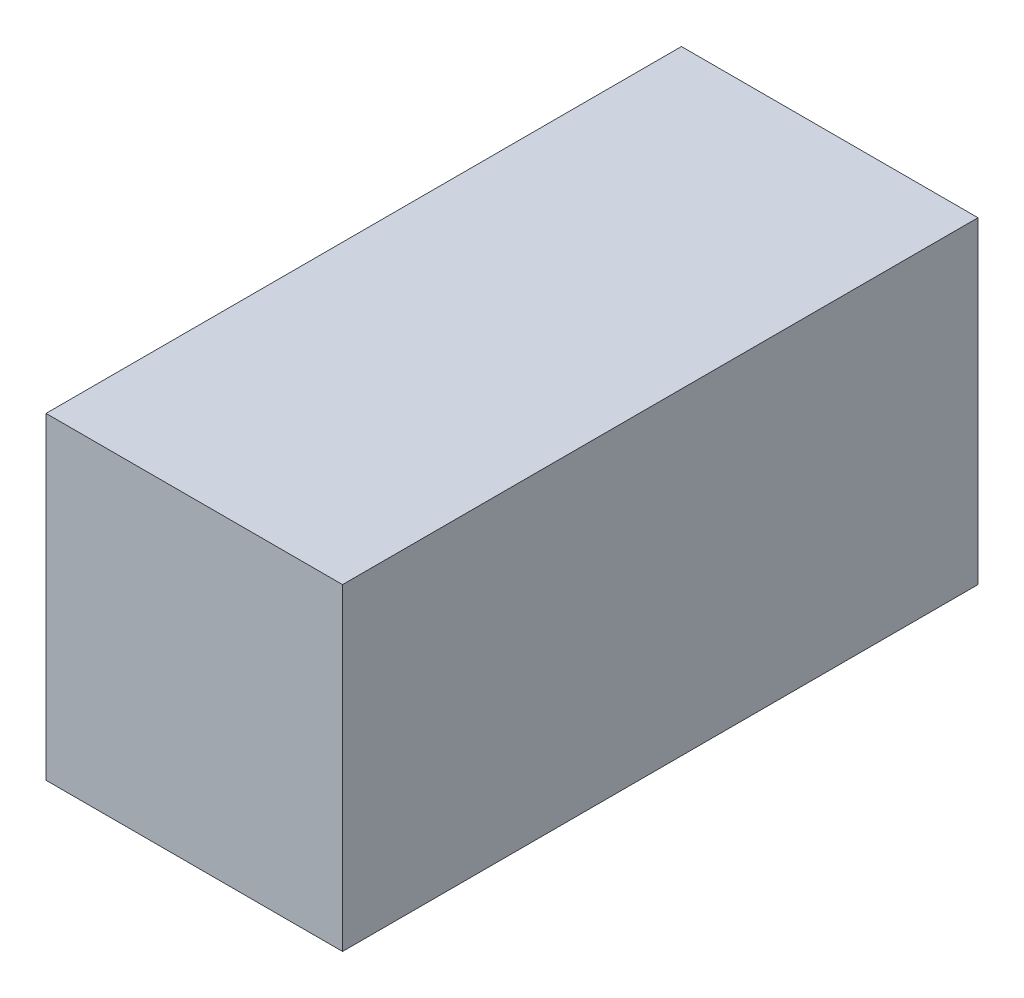
SolidWorks part; units mm, degrees
ref_plane "Front Plane" through (0, 0, 0) normal (0, 0, 1) x (1, 0, 0)
ref_plane "Top Plane" through (0, 0, 0) normal (0, 1, 0) x (1, 0, 0)
ref_plane "Right Plane" through (0, 0, 0) normal (1, 0, 0) x (0, 0, -1)
other "Configuration Table"
sketch "Sketch1" plane through (0, 0, 0) normal (0, 0, 1) x (1, 0, 0)
  line L1 (230, 405) -> (370, 405)
  line L2 (230, 405) -> (230, 555)
  line L3 (230, 555) -> (370, 555)
  line L4 (370, 405) -> (370, 555)
extrude "STORE_klape_kaset_kati_donmus_kap_2_1" add sketch "Sketch1" against normal blind 300 from offset 100 separate body
